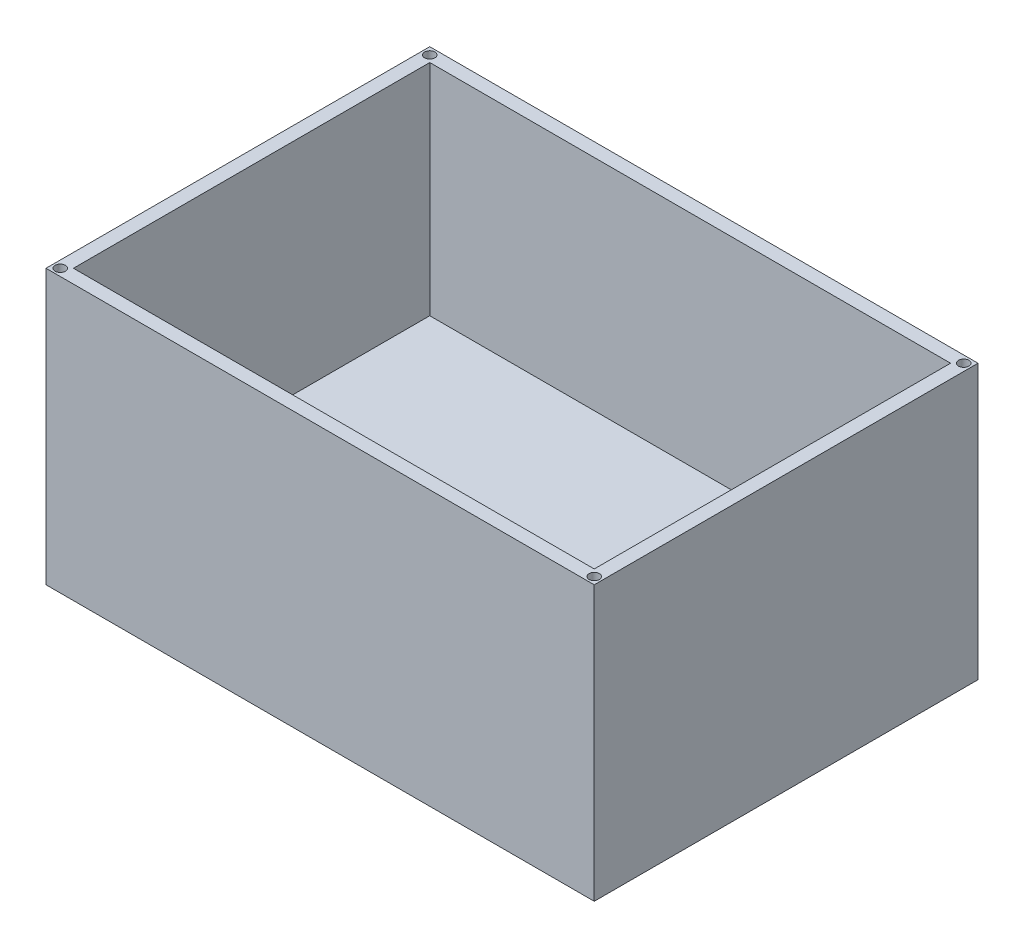
SolidWorks part; units mm, degrees
ref_plane "Front Plane" through (0, 0, 0) normal (0, 0, 1) x (1, 0, 0)
ref_plane "Top Plane" through (0, 0, 0) normal (0, 1, 0) x (1, 0, 0)
ref_plane "Right Plane" through (0, 0, 0) normal (1, 0, 0) x (0, 0, -1)
sketch "Sketch1" plane through (0, 0, 0) normal (0, 1, 0) x (1, 0, 0)
  line L1 (-127, -88.9) -> (127, -88.9)
  line L2 (-127, -88.9) -> (-127, 88.9)
  line L3 (-127, 88.9) -> (127, 88.9)
  line L4 (127, -88.9) -> (127, 88.9)
  line L5 (-127, -88.9) -> (127, 88.9) construction
  line L6 (-127, 88.9) -> (127, -88.9) construction
  point P0 (0, 0)
  dimension "D1" = 254
  dimension "D2" = 177.8
extrude "Boss-Extrude1" add sketch "Sketch1" along normal blind 127
sketch "Sketch2" plane through (0, 127, 0) normal (0, 1, 0) x (1, 0, 0)
  line L1 (-120.65, -82.55) -> (120.65, -82.55)
  line L2 (-120.65, -82.55) -> (-120.65, 82.55)
  line L3 (-120.65, 82.55) -> (120.65, 82.55)
  line L4 (120.65, -82.55) -> (120.65, 82.55)
  line L5 (-120.65, -82.55) -> (120.65, 82.55) construction
  line L6 (-120.65, 82.55) -> (120.65, -82.55) construction
  point P0 (0, 0)
  dimension "D1" = 165.1
  dimension "D2" = 241.3
extrude "Cut-Extrude1" cut sketch "Sketch2" against normal blind 101.6
sketch "Sketch10" plane through (0, 127, 0) normal (0, 1, 0) x (1, 0, 0)
  line L0 (127, 88.9) -> (-127, 88.9) construction
  line L3 (-127, 88.9) -> (-127, -88.9) construction
  point P0 (-123.698, 85.598)
  dimension "D1" = 3.302
  dimension "D2" = 3.302
hole_wizard "3/16 (0.1875) Diameter Hole3" positions "3DSketch1" profile "Sketch11" hole size "3/16" standard "ANSI Inch"
sketch3d "3DSketch1"
  point P0 (-123.698, 127, -85.598)
sketch "Sketch11" plane through (-123.698, 127, -85.598) normal (1, 0, 0) x (0, 0, 1)
  line L0 (0, 0) -> (0, 14.1308)
  line L1 (0, 14.1308) -> (2.3812, 12.7)
  line L2 (2.3812, 12.7) -> (2.3812, 0)
  line L5 (2.3812, 0) -> (0, 0)
  line L10 (0, 14.1308) -> (-2.3812, 12.7) construction
  line L11 (0, -6.35) -> (0, 107.95) construction
  dimension "Hole Dia." = 4.7625
  dimension "Hole Depth" = 12.7
  dimension "Drill Angle" = 118
sketch "Sketch12" plane through (0, 127, 0) normal (0, 1, 0) x (1, 0, 0)
  line L0 (127, 88.9) -> (-127, 88.9) construction
  line L1 (127, -88.9) -> (127, 88.9) construction
  point P0 (123.698, 85.598)
  dimension "D1" = 3.302
  dimension "D2" = 3.302
hole_wizard "3/16 (0.1875) Diameter Hole4" positions "3DSketch2" profile "Sketch13" hole size "3/16" standard "ANSI Inch"
sketch3d "3DSketch2"
  point P0 (123.698, 127, -85.598)
sketch "Sketch13" plane through (123.698, 127, -85.598) normal (1, 0, 0) x (0, 0, 1)
  line L0 (0, 0) -> (0, 14.1308)
  line L1 (0, 14.1308) -> (2.3812, 12.7)
  line L2 (2.3812, 12.7) -> (2.3812, 0)
  line L5 (2.3812, 0) -> (0, 0)
  line L10 (0, 14.1308) -> (-2.3812, 12.7) construction
  line L11 (0, -6.35) -> (0, 107.95) construction
  dimension "Hole Dia." = 4.7625
  dimension "Hole Depth" = 12.7
  dimension "Drill Angle" = 118
sketch "Sketch14" plane through (0, 127, 0) normal (0, 1, 0) x (1, 0, 0)
  line L0 (-127, -88.9) -> (127, -88.9) construction
  line L1 (127, -88.9) -> (127, 88.9) construction
  line L2 (-127, 88.9) -> (-127, -88.9) construction
  point P0 (123.698, -85.598)
  point P5 (-123.698, -85.598)
  dimension "D1" = 3.302
  dimension "D2" = 3.302
  dimension "D3" = 3.302
  dimension "D4" = 3.302
hole_wizard "3/16 (0.1875) Diameter Hole5" positions "3DSketch3" profile "Sketch15" hole size "3/16" standard "ANSI Inch"
sketch3d "3DSketch3"
  point P0 (-123.698, 127, 85.598)
sketch "Sketch15" plane through (-123.698, 127, 85.598) normal (1, 0, 0) x (0, 0, 1)
  line L0 (0, 0) -> (0, 14.1308)
  line L1 (0, 14.1308) -> (2.3812, 12.7)
  line L2 (2.3812, 12.7) -> (2.3812, 0)
  line L5 (2.3812, 0) -> (0, 0)
  line L10 (0, 14.1308) -> (-2.3812, 12.7) construction
  line L11 (0, -6.35) -> (0, 107.95) construction
  dimension "Hole Dia." = 4.7625
  dimension "Hole Depth" = 12.7
  dimension "Drill Angle" = 118
hole_wizard "3/16 (0.1875) Diameter Hole6" positions "3DSketch4" profile "Sketch16" hole size "3/16" standard "ANSI Inch"
sketch3d "3DSketch4"
  point P0 (123.698, 127, 85.598)
sketch "Sketch16" plane through (123.698, 127, 85.598) normal (1, 0, 0) x (0, 0, 1)
  line L0 (0, 0) -> (0, 14.1308)
  line L1 (0, 14.1308) -> (2.3812, 12.7)
  line L2 (2.3812, 12.7) -> (2.3812, 0)
  line L5 (2.3812, 0) -> (0, 0)
  line L10 (0, 14.1308) -> (-2.3812, 12.7) construction
  line L11 (0, -6.35) -> (0, 107.95) construction
  dimension "Hole Dia." = 4.7625
  dimension "Hole Depth" = 12.7
  dimension "Drill Angle" = 118
hole_wizard "11/64 (0.17188) Diameter Hole1" positions "Sketch17" profile "Sketch18" hole size "11/64" standard "ANSI Inch"
sketch "Sketch17" plane through (0, 0, -82.55) normal (0, 0, 1) x (1, 0, 0)
  point P0 (90.0009, 33.4019)
  point P6 (90.0009, 61.1158)
  point P8 (77.5076, 52.7357)
  point P10 (77.5076, 38.8562)
  point P17 (103.3569, 52.7357)
  point P19 (103.3569, 38.8562)
  point P21 (90.0009, 46.9779)
sketch "Sketch18" plane through (90.0009, 33.4019, -82.55) normal (1, 0, 0) x (0, -1, 0)
  line L0 (0, 0) -> (0, 6.35)
  line L1 (0, 6.35) -> (2.1829, 6.35)
  line L2 (2.1829, 6.35) -> (2.1829, 0)
  line L5 (2.1829, 0) -> (0, 0)
  line L11 (0, -6.35) -> (0, 107.95) construction
  dimension "Thru Hole Dia." = 4.3658
  dimension "Thru Hole Depth" = 6.35
